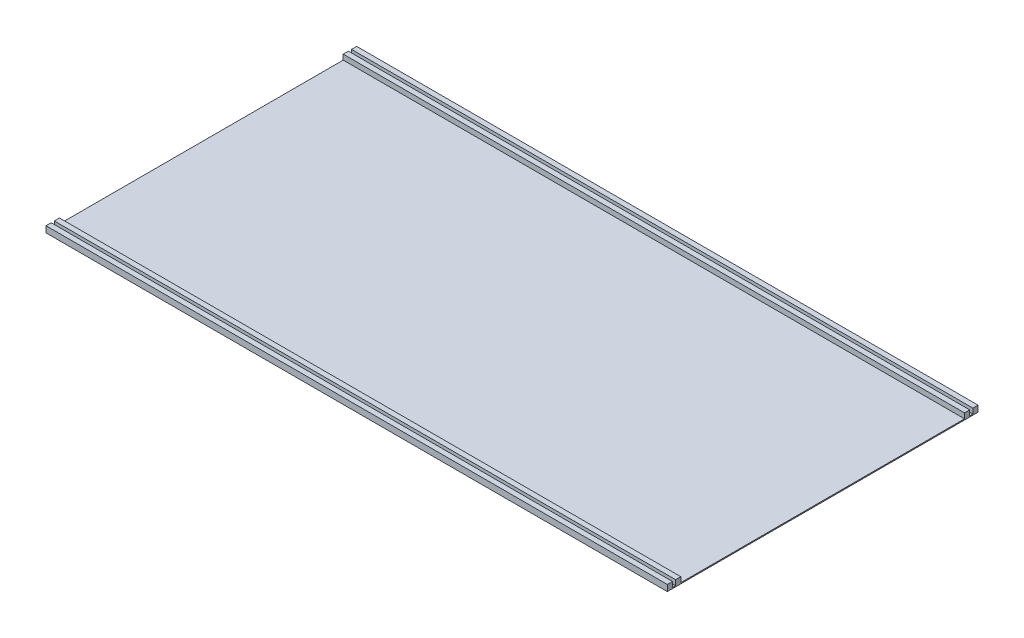
SolidWorks part; units mm, degrees
ref_plane "Front Plane" through (0, 0, 0) normal (0, 0, 1) x (1, 0, 0)
ref_plane "Top Plane" through (0, 0, 0) normal (0, 1, 0) x (1, 0, 0)
ref_plane "Right Plane" through (0, 0, 0) normal (1, 0, 0) x (0, 0, -1)
sketch "Sketch1" plane through (0, 0, 0) normal (0, 1, 0) x (1, 0, 0)
  line L1 (0, 0) -> (6000, 0)
  line L2 (0, 0) -> (0, -3000)
  line L3 (0, -3000) -> (6000, -3000)
  line L4 (6000, 0) -> (6000, -3000)
  dimension "D1" = 3000
  dimension "D2" = 6000
extrude "Boss-Extrude1" add sketch "Sketch1" along normal blind 10
sketch "Sketch3" plane through (0, 10, 0) normal (0, 1, 0) x (1, 0, 0)
  line L0 (6000, -3000) -> (6000, 0) construction
  line L1 (0, -3000) -> (6000, -3000)
  line L2 (0, -3000) -> (0, -2950)
  line L3 (0, -2950) -> (6000, -2950)
  line L4 (6000, -3000) -> (6000, -2950)
  line L5 (0, 0) -> (0, -3000) construction
  line L6 (0, -2920) -> (6000, -2920)
  line L7 (0, -2920) -> (0, -2870)
  line L8 (0, -2870) -> (6000, -2870)
  line L9 (6000, -2920) -> (6000, -2870)
  dimension "D1" = 50
  dimension "D2" = 50
  dimension "D3" = 30
extrude "Boss-Extrude2" add sketch "Sketch3" along normal blind 50
sketch "Sketch4" plane through (0, 10, 0) normal (0, 1, 0) x (1, 0, 0)
  line L0 (6000, -2870) -> (6000, 0) construction
  line L1 (0, 0) -> (6000, 0)
  line L2 (0, 0) -> (0, -50)
  line L3 (0, -50) -> (6000, -50)
  line L4 (6000, 0) -> (6000, -50)
  line L5 (0, 0) -> (0, -2870) construction
  line L6 (0, -80) -> (6000, -80)
  line L7 (0, -80) -> (0, -130)
  line L8 (0, -130) -> (6000, -130)
  line L9 (6000, -80) -> (6000, -130)
  dimension "D1" = 50
  dimension "D2" = 50
  dimension "D3" = 30
extrude "Boss-Extrude3" add sketch "Sketch4" along normal blind 50
